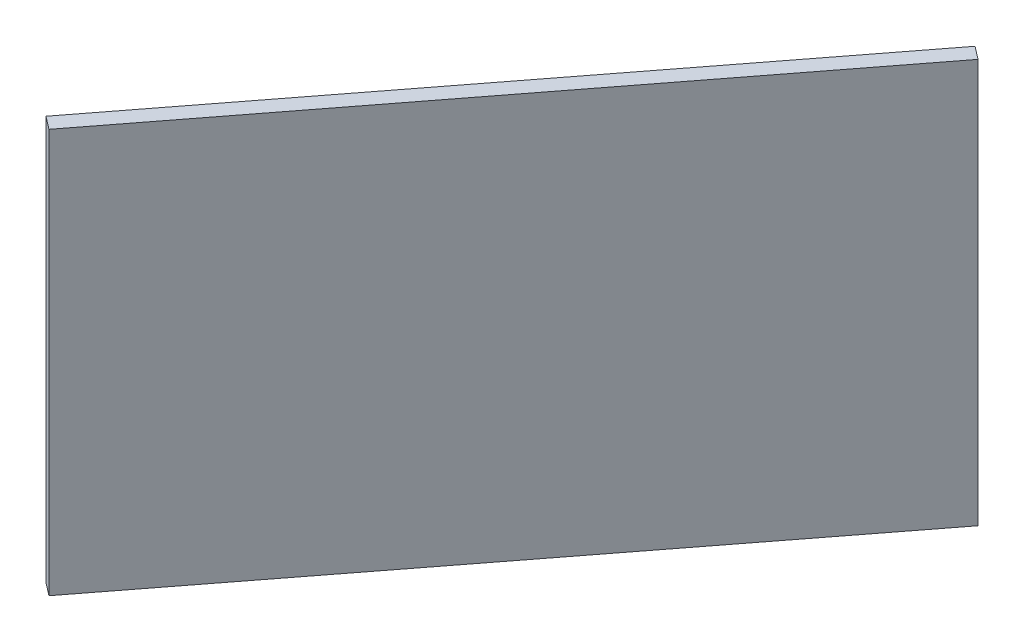
SolidWorks part; units mm, degrees
ref_plane "Front Plane" through (0, 0, 0) normal (0, 0, 1) x (1, 0, 0)
ref_plane "Top Plane" through (0, 0, 0) normal (0, 1, 0) x (1, 0, 0)
ref_plane "Right Plane" through (0, 0, 0) normal (1, 0, 0) x (0, 0, -1)
sketch "Sketch1" plane through (0, 0, 0) normal (0, 1, 0) x (1, 0, 0)
  line L0 (0, -65) -> (0, 0) construction
  line L1 (0, -55) -> (0, 55) construction
  line L2 (0, 0) -> (50, 0) construction
  line L3 (0, -65) -> (50, 0) construction
  line L4 (-0.7926, -64.3903) -> (49.2074, 0.6097)
  line L5 (49.2074, 0.6097) -> (50.7926, -0.6097)
  line L6 (50.7926, -0.6097) -> (0.7926, -65.6097)
  line L7 (0.7926, -65.6097) -> (-0.7926, -64.3903)
  dimension "D1" = 65
  dimension "D2" = 50
  dimension "D3" = 2
extrude "Boss-Extrude1" add sketch "Sketch1" along normal blind 50
